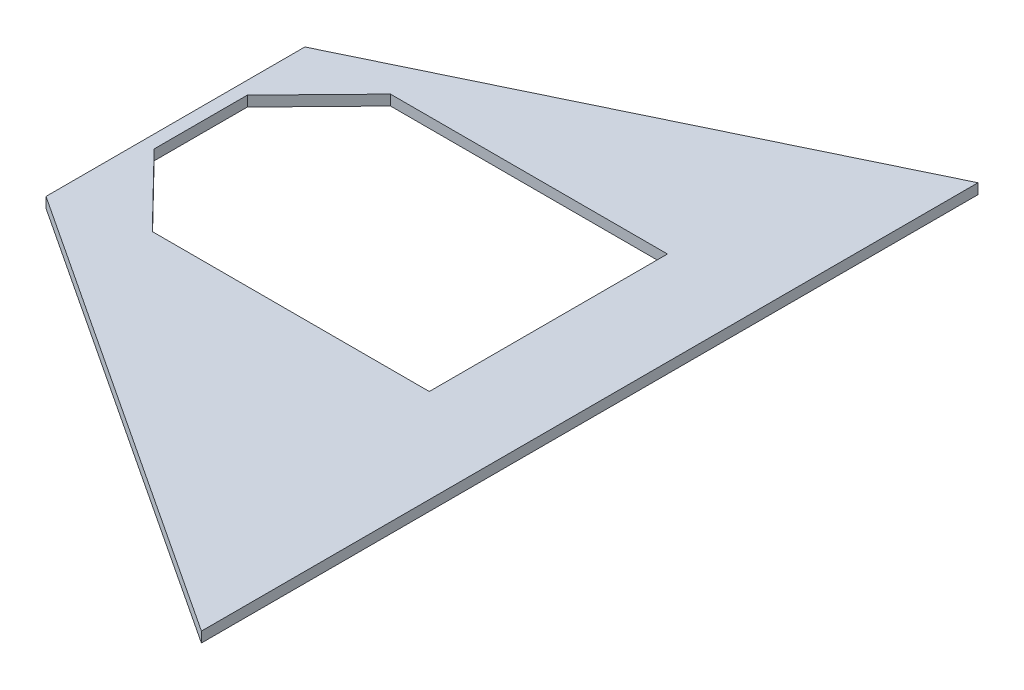
SolidWorks part; units mm, degrees
material "Сосна"
ref_plane "Спереди" through (0, 0, 0) normal (0, 0, 1) x (1, 0, 0)
ref_plane "Сверху" through (0, 0, 0) normal (0, 1, 0) x (1, 0, 0)
ref_plane "Справа" through (0, 0, 0) normal (1, 0, 0) x (0, 0, -1)
sketch3d "Трехмерный эскиз1"
  line L2 (-133.6241, 10, -49.1612) -> (-133.6241, 10, 42.8388) construction
  line L3 (-133.6241, 10, -49.1612) -> (-26.6241, 10, 42.8388) construction
  line L6 (-133.6241, 10, 42.8388) -> (-26.6241, 10, -49.1612) construction
  line L12 (9.5203, 10, -132.9874) -> (9.5203, 10, 167.0126)
  line L13 (9.5203, 10, 167.0126) -> (-165.9256, 10, 51.6057)
  line L14 (-165.9256, 10, 51.6057) -> (-165.9256, 10, -48.3943)
  line L15 (-165.9256, 10, -48.3943) -> (9.5203, 10, -132.9874)
  line L17 (-133.6241, 10, -49.1612) -> (-26.6241, 10, -49.1612)
  line L19 (-160.9256, 10, -21.1612) -> (-133.6241, 10, -49.1612)
  line L20 (-160.9256, 10, -21.1612) -> (-160.9256, 10, 14.8388)
  line L21 (-160.9256, 10, 14.8388) -> (-133.6241, 10, 42.8388)
  line L23 (-133.6241, 10, 42.8388) -> (-26.6241, 10, 42.8388)
  line L24 (-26.6241, 10, 42.8388) -> (-26.6241, 10, -49.1612)
  dimension "D1" = 10
  dimension "D2" = 36
  dimension "D18" = 134.3015
  dimension "D5" = 92
  dimension "D6" = 107
  dimension "D7" = 5
  dimension "D12" = 300
  dimension "D13" = 100
  dimension "D14" = 210
  dimension "D15" = 194.7749
extrude "Бобышка-Вытянуть2" add sketch "Трехмерный эскиз1" along direction (0, 1, 0) on the side against the normal blind 4
